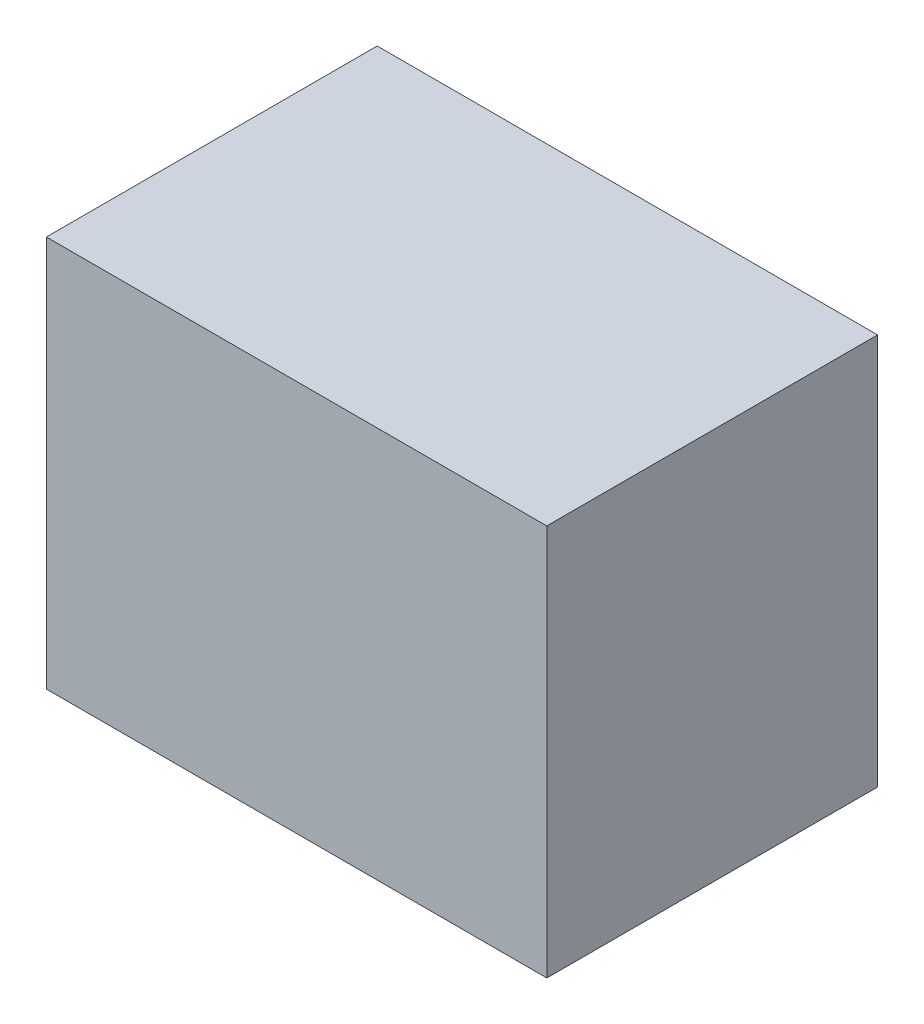
SolidWorks part; units mm, degrees
ref_plane "Front Plane" through (0, 0, 0) normal (0, 0, 1) x (1, 0, 0)
ref_plane "Top Plane" through (0, 0, 0) normal (0, 1, 0) x (1, 0, 0)
ref_plane "Right Plane" through (0, 0, 0) normal (1, 0, 0) x (0, 0, -1)
sketch "Sketch1" plane through (0, 0, 0) normal (0, 0, 1) x (1, 0, 0)
  line L1 (-54.1413, 558.5961) -> (704.6837, 558.5961)
  line L2 (-54.1413, 558.5961) -> (-54.1413, -35.1289)
  line L3 (-54.1413, -35.1289) -> (704.6837, -35.1289)
  line L4 (704.6837, 558.5961) -> (704.6837, -35.1289)
extrude "Boss-Extrude1" add sketch "Sketch1" along normal blind 501.65
